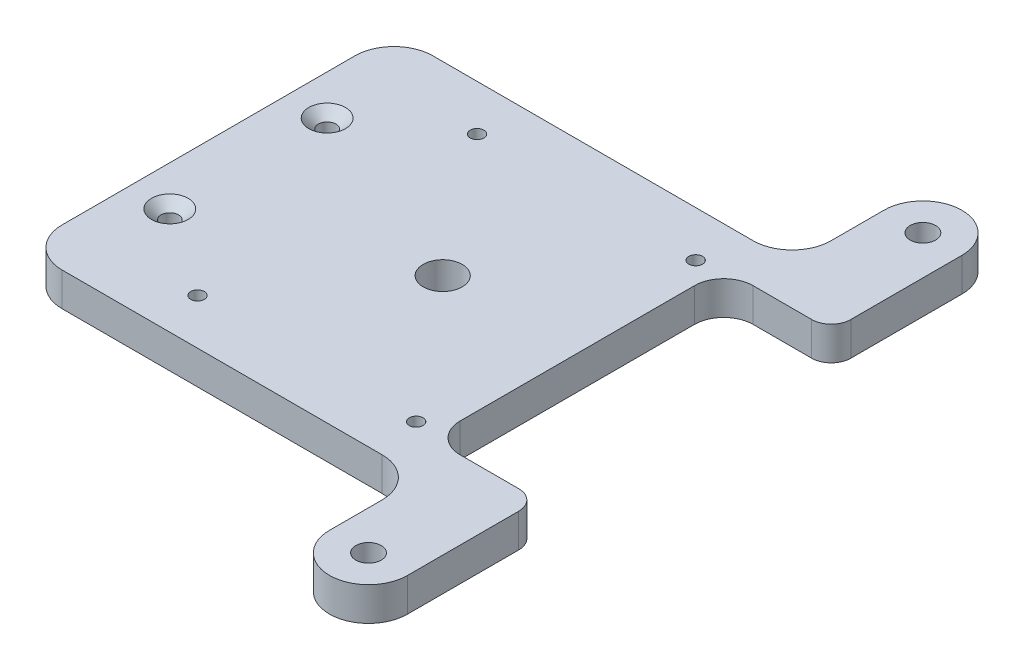
SolidWorks part; units mm, degrees
ref_plane "Alzado" through (0, 0, 0) normal (0, 0, 1) x (1, 0, 0)
ref_plane "Planta" through (0, 0, 0) normal (0, 1, 0) x (1, 0, 0)
ref_plane "Vista lateral" through (0, 0, 0) normal (1, 0, 0) x (0, 0, -1)
sketch "Croquis1" plane through (0, 4, 0) normal (0, 1, 0) x (1, 0, 0)
  line L0 (317, -47.5) -> (317, -71) construction
  line L1 (337, -71) -> (337, 71) construction
  line L2 (317, 71) -> (317, 47.5) construction
  line L3 (317, -47.5) -> (317, -71)
  line L4 (337, -71) -> (337, 71)
  line L5 (317, 71) -> (317, 47.5)
  line L6 (317, 47.5) -> (215, 47.5)
  line L7 (215, 47.5) -> (215, -47.5)
  line L8 (215, -47.5) -> (317, -47.5)
  arc A0 (317, -71) -> (337, -71) centre (327, -71) ccw construction
  arc A1 (337, 71) -> (317, 71) centre (327, 71) ccw construction
  arc A2 (317, -71) -> (337, -71) centre (327, -71) ccw
  arc A3 (337, 71) -> (317, 71) centre (327, 71) ccw
  arc A4 (248, 34.55) -> (248, 37.05) centre (248, 35.8) ccw construction
  arc A5 (248, 37.05) -> (248, 34.55) centre (248, 35.8) ccw construction
  arc A6 (304, 34.55) -> (304, 37.05) centre (304, 35.8) ccw construction
  arc A7 (304, 37.05) -> (304, 34.55) centre (304, 35.8) ccw construction
  arc A8 (304, -37.05) -> (304, -34.55) centre (304, -35.8) ccw construction
  arc A9 (304, -34.55) -> (304, -37.05) centre (304, -35.8) ccw construction
  arc A10 (248, -37.05) -> (248, -34.55) centre (248, -35.8) ccw construction
  arc A11 (248, -34.55) -> (248, -37.05) centre (248, -35.8) ccw construction
  arc A12 (248, 34.55) -> (248, 37.05) centre (248, 35.8) ccw construction
  arc A13 (248, 37.05) -> (248, 34.55) centre (248, 35.8) ccw construction
  arc A14 (304, 34.55) -> (304, 37.05) centre (304, 35.8) ccw construction
  arc A15 (304, 37.05) -> (304, 34.55) centre (304, 35.8) ccw construction
  arc A16 (304, -37.05) -> (304, -34.55) centre (304, -35.8) ccw construction
  arc A17 (304, -34.55) -> (304, -37.05) centre (304, -35.8) ccw construction
  arc A18 (248, -37.05) -> (248, -34.55) centre (248, -35.8) ccw construction
  arc A19 (248, -34.55) -> (248, -37.05) centre (248, -35.8) ccw construction
  arc A20 (248, -37.55) -> (248, -34.05) centre (248, -35.8) ccw
  arc A21 (248, -34.05) -> (248, -37.55) centre (248, -35.8) ccw
  circle A24 centre (327, 71) radius 3 construction
  circle A25 centre (327, -71) radius 3 construction
  circle A26 centre (327, 71) radius 3 construction
  circle A27 centre (327, -71) radius 3 construction
  arc A28 (248, 34.05) -> (248, 37.55) centre (248, 35.8) ccw
  arc A29 (248, 37.55) -> (248, 34.05) centre (248, 35.8) ccw
  arc A30 (304, 37.55) -> (304, 34.05) centre (304, 35.8) ccw
  arc A31 (304, 34.05) -> (304, 37.55) centre (304, 35.8) ccw
  arc A32 (304, -37.55) -> (304, -34.05) centre (304, -35.8) ccw
  arc A33 (304, -34.05) -> (304, -37.55) centre (304, -35.8) ccw
  circle A34 centre (327, 71) radius 3.25
  circle A35 centre (327, -71) radius 3.25
  dimension "D4" = 6.5
  dimension "D1" = 102
  dimension "D2" = 0.5
  dimension "D3" = 0.5
extrude "Saliente-Extruir1" add sketch "Croquis1" along normal blind 8.6
fillet "Redondeo1" radius 10 4 edges at (215, 8.3, -47.5) (215, 8.3, 47.5) (317, 8.3, 47.5) (317, 8.3, -47.5)
sketch "Croquis4" plane through (0, 12.6, 0) normal (0, 1, 0) x (1, 0, 0)
  circle A0 centre (225.25, 20.15) radius 2 construction
  circle A1 centre (225.25, -20.15) radius 2 construction
  circle A2 centre (317, -30) radius 4.5 construction
  circle A3 centre (317, 30) radius 4.5 construction
  circle A4 centre (225.25, 20.15) radius 2
  circle A5 centre (225.25, -20.15) radius 2
  circle A6 centre (317, -30) radius 4.5
  circle A7 centre (317, 30) radius 4.5
hole_wizard "Avellanado para tornillo con cabeza plana avellanada de M41" positions "Croquis14" profile "Croquis16" countersink size "M4" standard "DIN" end condition through all
sketch "Croquis14" plane through (0, 12.6, 0) normal (0, 1, 0) x (1, 0, 0)
  point P0 (225.25, -20.15)
  point P3 (225.25, 20.15)
sketch "Croquis16" plane through (225.25, 12.6, 20.15) normal (1, 0, 0) x (0, 0, 1)
  line L0 (0, 0) -> (0, 8.6)
  line L1 (0, 8.6) -> (2.25, 8.6)
  line L2 (2.25, 8.6) -> (2.25, 2.45)
  line L3 (2.25, 2.45) -> (4.7, 0)
  line L5 (4.7, 0) -> (0, 0)
  line L6 (-2.25, 2.45) -> (-4.7, 0) construction
  line L11 (0, -6.35) -> (0, 107.95) construction
  dimension "Diámetro de taladro hasta el siguiente" = 4.5
  dimension "Profundidad de taladro hasta el siguiente" = 8.6
  dimension "Diámetro de avellanado cercano" = 9.4
  dimension "Ángulo de avellanado cercano" = 90
sketch "Croquis17" plane through (0, 12.6, 0) normal (0, 1, 0) x (1, 0, 0)
  circle A0 centre (275, 0) radius 2.5 construction
  circle A1 centre (275, 0) radius 5
  dimension "D2" = 2.5
  dimension "D1" = 5
extrude "Cortar-Extruir1" cut sketch "Croquis17" against normal blind 10
sketch "Croquis23" plane through (0, 12.6, 0) normal (0, 1, 0) x (1, 0, 0)
  circle A0 centre (317, 30) radius 4.5 construction
  circle A1 centre (317, -30) radius 4.5 construction
  circle A2 centre (317, 30) radius 4.5
  circle A3 centre (317, -30) radius 4.5
hole_wizard "Refrentado para tornillo con cabeza plana de M84" positions "Croquis24" profile "Croquis26" counterbore size "M8" standard "DIN"
sketch "Croquis24" plane through (0, 12.6, 0) normal (0, 1, 0) x (1, 0, 0)
  point P0 (317, 30)
  point P3 (317, -30)
sketch "Croquis26" plane through (317, 12.6, -30) normal (1, 0, 0) x (0, 0, 1)
  line L0 (0, 0) -> (0, 7.5039)
  line L1 (0, 7.5039) -> (4.5, 4.8)
  line L2 (4.5, 4.8) -> (4.5, 8.6)
  line L3 (4.5, 8.6) -> (7.5, 8.6)
  line L5 (7.5, 8.6) -> (7.5, 0.025)
  line L6 (7.5, 0.025) -> (7.525, 0)
  line L7 (7.525, 0) -> (0, 0)
  line L8 (-7.5, 0.025) -> (-7.525, 0) construction
  line L10 (0, 7.5039) -> (-4.5, 4.8) construction
  line L11 (0, -6.35) -> (0, 107.95) construction
  dimension "Diámetro de taladro" = 9
  dimension "Profundidad de taladro" = 4.8
  dimension "Diámetro de refrentado" = 15
  dimension "Profundidad de refrentado" = 8.6
  dimension "Diámetro de avellanado cercano" = 15.05
  dimension "Ángulo de avellanado cercano" = 90
  dimension "Ángulo de perforador" = 118
sketch "Croquis27" plane through (0, 12.6, 0) normal (0, 1, 0) x (1, 0, 0)
  line L0 (317, 37.525) -> (337, 37.525)
  line L1 (337, -71) -> (337, 71) construction
  line L2 (337, 37.525) -> (337, -37.525)
  line L3 (337, -37.525) -> (317, -37.525)
  line L4 (309.475, -30) -> (309.475, 30)
  circle A0 centre (317, -30) radius 7.525 construction
  circle A1 centre (317, 30) radius 7.525 construction
  arc A2 (309.475, -30) -> (317, -37.525) centre (317, -30) ccw
  arc A3 (317, 37.525) -> (309.475, 30) centre (317, 30) ccw
extrude "Cortar-Extruir3" cut sketch "Croquis27" against normal blind 10
fillet "Redondeo3" radius 5 2 edges at (337, 8.3, 37.525) (337, 8.3, -37.525)
hole_wizard "Refrentado para tornillo con cabeza plana de M31" positions "Croquis28" profile "Croquis29" counterbore size "M3" standard "DIN" end condition through all
sketch "Croquis28" plane through (0, 4, 0) normal (0, -1, 0) x (-1, 0, 0)
  point P0 (-248, -35.8)
  point P3 (-304, -35.8)
  point P6 (-304, 35.8)
  point P9 (-248, 35.8)
sketch "Croquis29" plane through (248, 4, 35.8) normal (1, 0, 0) x (0, 0, -1)
  line L0 (0, 0) -> (0, 8.6)
  line L1 (0, 8.6) -> (1.7, 8.6)
  line L3 (1.7, 8.6) -> (1.7, 4.3)
  line L4 (1.7, 4.3) -> (3.25, 4.3)
  line L5 (3.25, 4.3) -> (3.25, 0)
  line L7 (3.25, 0) -> (0, 0)
  line L11 (0, -6.35) -> (0, 107.95) construction
  dimension "Diámetro de taladro hasta el siguiente" = 3.4
  dimension "Profundidad de taladro hasta el siguiente" = 8.6
  dimension "Diámetro de refrentado" = 6.5
  dimension "Profundidad de refrentado" = 4.3
